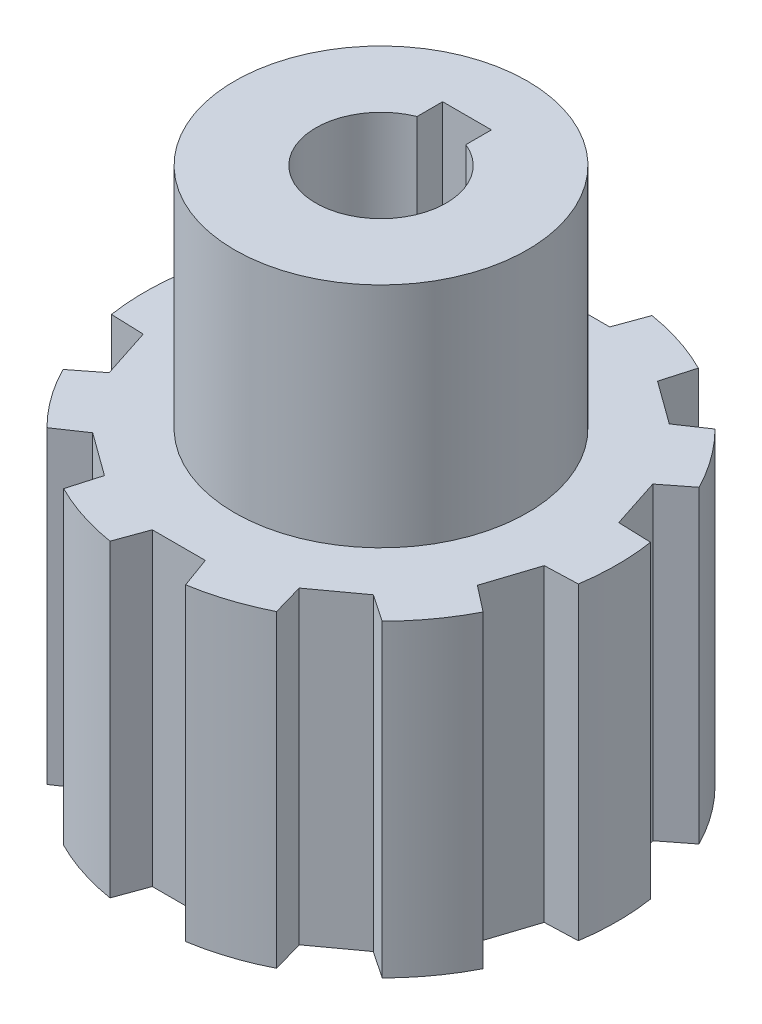
SolidWorks part; units mm, degrees
ref_plane "Front Plane" through (0, 0, 0) normal (0, 0, 1) x (1, 0, 0)
ref_plane "Top Plane" through (0, 0, 0) normal (0, 1, 0) x (1, 0, 0)
ref_plane "Right Plane" through (0, 0, 0) normal (1, 0, 0) x (0, 0, -1)
sketch "Sketch2" plane through (0, 0, 0) normal (0, 1, 0) x (1, 0, 0)
  line L0 (7.3355, -10.3439) -> (9.9741, -8.4269)
  line L1 (9.9741, -8.4269) -> (11.6548, -9.5605)
  line L2 (14.2651, -5.9678) -> (12.6676, -4.7197)
  line L3 (12.6676, -4.7197) -> (13.6754, -1.6178)
  line L4 (13.6754, -1.6178) -> (15.7014, -1.5471)
  line L5 (15.7014, 2.8938) -> (13.6754, 2.9645)
  line L6 (13.6754, 2.9645) -> (12.6676, 6.0664)
  line L7 (12.6676, 6.0664) -> (14.2651, 7.3145)
  line L8 (11.6548, 10.9072) -> (9.9741, 9.7736)
  line L9 (9.9741, 9.7736) -> (7.3355, 11.6906)
  line L10 (7.3355, 11.6906) -> (7.8943, 13.6394)
  line L11 (3.6708, 15.0117) -> (2.9775, 13.1067)
  line L12 (2.9775, 13.1067) -> (-0.284, 13.1067)
  line L13 (-0.284, 13.1067) -> (-0.9774, 15.0117)
  line L14 (-5.2009, 13.6394) -> (-4.6421, 11.6906)
  line L15 (-4.6421, 11.6906) -> (-7.2807, 9.7736)
  line L16 (-7.2807, 9.7736) -> (-8.9614, 10.9072)
  line L17 (-11.5716, 7.3145) -> (-9.9741, 6.0664)
  line L18 (-9.9741, 6.0664) -> (-10.982, 2.9645)
  line L19 (-10.982, 2.9645) -> (-13.008, 2.8938)
  line L20 (-13.008, -1.5471) -> (-10.982, -1.6178)
  line L21 (-10.982, -1.6178) -> (-9.9741, -4.7197)
  line L22 (-9.9741, -4.7197) -> (-11.5716, -5.9678)
  line L23 (-8.9614, -9.5605) -> (-7.2807, -8.4269)
  line L24 (-7.2807, -8.4269) -> (-4.6421, -10.3439)
  line L25 (-4.6421, -10.3439) -> (-5.2009, -12.2926)
  line L26 (-0.9774, -13.6649) -> (-0.284, -11.7599)
  line L27 (-0.284, -11.7599) -> (2.9775, -11.7599)
  line L28 (2.9775, -11.7599) -> (3.6708, -13.6649)
  line L29 (7.8943, -12.2926) -> (7.3355, -10.3439)
  arc A0 (11.6548, -9.5605) -> (14.2651, -5.9678) centre (1.3467, 0.6734) ccw
  arc A1 (15.7014, -1.5471) -> (15.7014, 2.8938) centre (1.3467, 0.6734) ccw
  arc A2 (14.2651, 7.3145) -> (11.6548, 10.9072) centre (1.3467, 0.6734) ccw
  arc A3 (7.8943, 13.6394) -> (3.6708, 15.0117) centre (1.3467, 0.6734) ccw
  arc A4 (-0.9774, 15.0117) -> (-5.2009, 13.6394) centre (1.3467, 0.6734) ccw
  arc A5 (-8.9614, 10.9072) -> (-11.5716, 7.3145) centre (1.3467, 0.6734) ccw
  arc A6 (-13.008, 2.8938) -> (-13.008, -1.5471) centre (1.3467, 0.6734) ccw
  arc A7 (-11.5716, -5.9678) -> (-8.9614, -9.5605) centre (1.3467, 0.6734) ccw
  arc A8 (-5.2009, -12.2926) -> (-0.9774, -13.6649) centre (1.3467, 0.6734) ccw
  arc A9 (3.6708, -13.6649) -> (7.8943, -12.2926) centre (1.3467, 0.6734) ccw
extrude "Boss-Extrude1" add sketch "Sketch2" along normal blind 19
sketch "Sketch3" plane through (0, 19, 0) normal (0, 1, 0) x (1, 0, 0)
  line L0 (1.3467, 13.1067) -> (1.3467, -11.7599) construction
  line L1 (2.9775, 13.1067) -> (-0.284, 13.1067) construction
  line L2 (-0.284, -11.7599) -> (2.9775, -11.7599) construction
  line L3 (13.1715, 4.5155) -> (-10.4781, -3.1687) construction
  line L4 (13.6754, 2.9645) -> (12.6676, 6.0664) construction
  line L5 (-10.982, -1.6178) -> (-9.9741, -4.7197) construction
  line L6 (8.6548, -9.3854) -> (-5.9614, 10.7321) construction
  line L7 (7.3355, -10.3439) -> (9.9741, -8.4269) construction
  line L8 (-4.6421, 11.6906) -> (-7.2807, 9.7736) construction
  circle A0 centre (1.3467, 0.6734) radius 4.01
  point P18 (1.3467, 0.6734)
  dimension "D1" = 8.02
extrude "Cut-Extrude1" cut sketch "Sketch3" against normal through all
sketch "Sketch4" plane through (0, 19, 0) normal (0, 1, 0) x (1, 0, 0)
  line L0 (1.3467, 13.1067) -> (1.3467, -11.7599) construction
  line L1 (2.9775, 13.1067) -> (-0.284, 13.1067) construction
  line L2 (-0.284, -11.7599) -> (2.9775, -11.7599) construction
  line L4 (-0.1533, 1.6127) -> (2.8467, 1.6127)
  line L5 (-0.1533, 1.6127) -> (-0.1533, 5.9634)
  line L6 (-0.1533, 5.9634) -> (2.8467, 5.9634)
  line L7 (2.8467, 1.6127) -> (2.8467, 5.9634)
  line L8 (-0.1533, 1.6127) -> (2.8467, 5.9634) construction
  line L9 (-0.1533, 5.9634) -> (2.8467, 1.6127) construction
  circle A0 centre (1.3467, 0.6734) radius 4.01 construction
  point P6 (1.3467, -3.3366)
  point P7 (1.3467, 3.788)
  dimension "D1" = 3
  dimension "D2" = 9.3
extrude "Cut-Extrude2" cut sketch "Sketch4" against normal through all
sketch "Sketch5" plane through (0, 19, 0) normal (0, 1, 0) x (1, 0, 0)
  line L0 (2.8467, 4.3922) -> (2.8467, 5.9634) construction
  line L1 (2.8467, 5.9634) -> (-0.1533, 5.9634) construction
  line L2 (-0.1533, 5.9634) -> (-0.1533, 4.3922) construction
  line L3 (2.8467, 4.3922) -> (2.8467, 5.9634)
  line L4 (2.8467, 5.9634) -> (-0.1533, 5.9634)
  line L5 (-0.1533, 5.9634) -> (-0.1533, 4.3922)
  arc A0 (-0.1533, 4.3922) -> (2.8467, 4.3922) centre (1.3467, 0.6734) ccw construction
  arc A1 (-0.1533, 4.3922) -> (2.8467, 4.3922) centre (1.3467, 0.6734) ccw
  circle A2 centre (1.3467, 0.6734) radius 9
  dimension "D1" = 18
extrude "Boss-Extrude2" add sketch "Sketch5" along normal blind 14
sketch "Sketch7" plane through (0, 0, -13.1067) normal (0, 0, -1) x (-1, 0, 0)
  line L0 (-1.3467, 33) -> (-1.3467, 0) construction
  line L1 (-2.8467, 33) -> (0.1533, 33) construction
  line L2 (-2.9775, 0) -> (0.284, 0) construction
  line L5 (-2.9775, 19) -> (0.284, 19) construction
  point P6 (-1.3467, 16.7)
  dimension "D1" = 2.3
hole_wizard "M3x0.5 Tapped Hole1" positions "3DSketch1" profile "Sketch8" tap size "M3x0.5" standard "ANSI Metric"
sketch3d "3DSketch1"
  point P0 (1.3467, 16.7, -13.1067)
cosmetic thread "Hole Thread1" parameters "D1"=7.1433, "D2"=3
sketch "Sketch8" plane through (1.3467, 16.7, -13.1067) normal (1, 0, 0) x (0, 1, 0)
  line L0 (0, 0) -> (0, 10.7511)
  line L1 (0, 10.7511) -> (1.25, 10)
  line L2 (1.25, 10) -> (1.25, 0)
  line L5 (1.25, 0) -> (0, 0)
  line L10 (0, 10.7511) -> (-1.25, 10) construction
  line L11 (0, -6.35) -> (0, 107.95) construction
  dimension "Tap Drill Dia." = 2.5
  dimension "Tap Drill Depth" = 10
  dimension "Drill Angle" = 118
